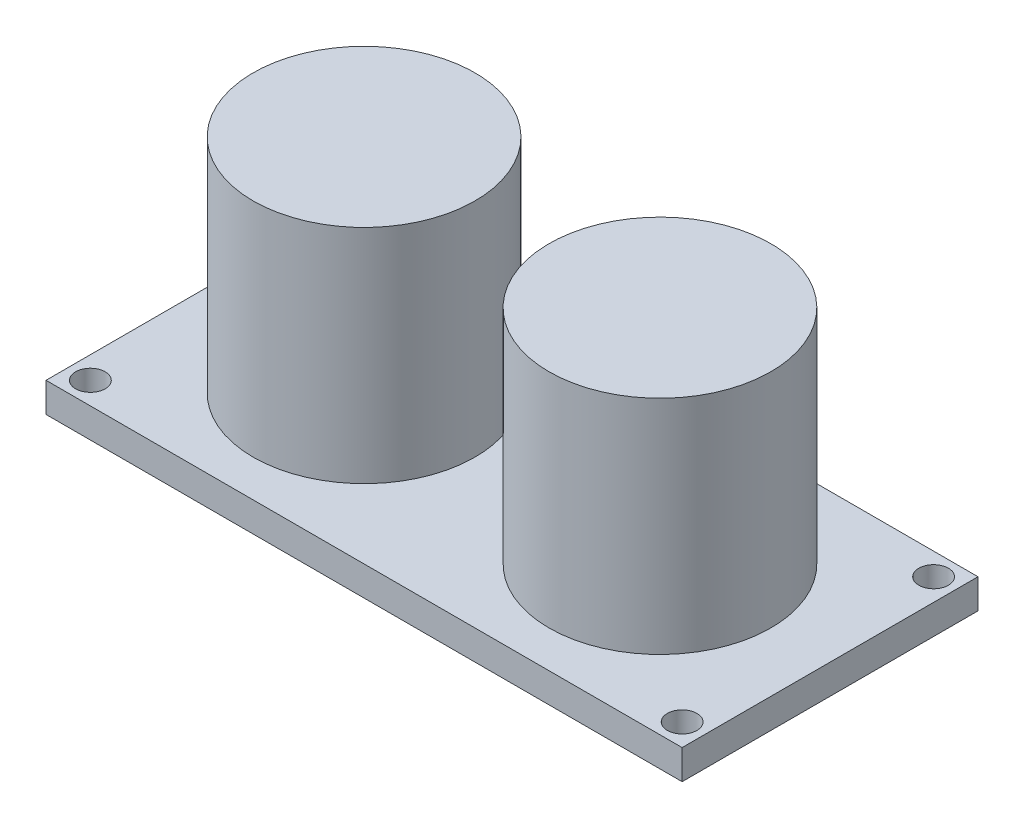
SolidWorks part; units mm, degrees
ref_plane "Front Plane" through (0, 0, 0) normal (0, 0, 1) x (1, 0, 0)
ref_plane "Top Plane" through (0, 0, 0) normal (0, 1, 0) x (1, 0, 0)
ref_plane "Right Plane" through (0, 0, 0) normal (1, 0, 0) x (0, 0, -1)
sketch "Sketch1" plane through (0, 0, 0) normal (0, 1, 0) x (1, 0, 0)
  line L1 (-19.6157, 8.4087) -> (23.3843, 8.4087)
  line L2 (-19.6157, 8.4087) -> (-19.6157, -11.5913)
  line L3 (-19.6157, -11.5913) -> (23.3843, -11.5913)
  line L4 (23.3843, 8.4087) -> (23.3843, -11.5913)
  dimension "D1" = 43
  dimension "D2" = 20
extrude "Boss-Extrude1" add sketch "Sketch1" along normal blind 2
sketch "Sketch2" plane through (0, 2, 0) normal (0, 1, 0) x (1, 0, 0)
  line L0 (-19.6157, 8.4087) -> (-19.6157, -11.5913) construction
  line L1 (23.3843, -11.5913) -> (23.3843, 8.4087) construction
  line L3 (23.3843, 8.4087) -> (-19.6157, 8.4087) construction
  line L4 (-19.6157, -11.5913) -> (23.3843, -11.5913) construction
  circle A0 centre (-18.1157, -10.0913) radius 1
  circle A1 centre (21.8843, -10.0913) radius 1
  circle A2 centre (-18.1157, 6.9087) radius 1
  circle A3 centre (21.8843, 6.9087) radius 1
  dimension "D1" = 1.5
  dimension "D3" = 1.5
  dimension "D5" = 1.5
  dimension "D6" = 1.5
  dimension "D2" = 1.5
  dimension "D4" = 1.5
  dimension "D7" = 1.5
  dimension "D8" = 1.5
extrude "Cut-Extrude1" cut sketch "Sketch2" against normal blind 2
sketch "Sketch3" plane through (0, 2, 0) normal (0, 1, 0) x (1, 0, 0)
  line L0 (1.8843, 8.4087) -> (1.8843, -11.5913) construction
  line L1 (23.3843, 8.4087) -> (-19.6157, 8.4087) construction
  line L2 (-19.6157, -11.5913) -> (23.3843, -11.5913) construction
  circle A0 centre (11.8843, -1.5913) radius 7.5
  circle A1 centre (-8.1157, -1.5913) radius 7.5
  dimension "D1" = 10
  dimension "D2" = 10
extrude "Boss-Extrude2" add sketch "Sketch3" along normal blind 15
